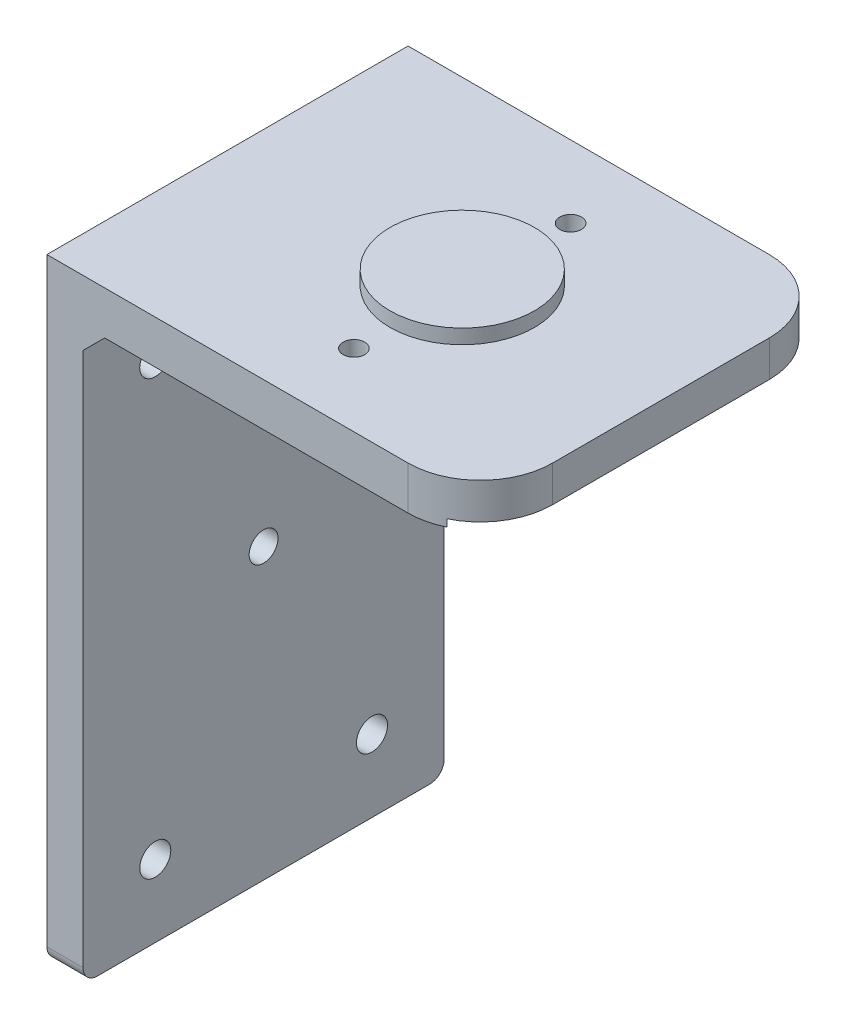
SolidWorks part; units mm, degrees
ref_plane "前视基准面" through (0, 0, 0) normal (0, 0, 1) x (1, 0, 0)
ref_plane "上视基准面" through (0, 0, 0) normal (0, 1, 0) x (1, 0, 0)
ref_plane "右视基准面" through (0, 0, 0) normal (1, 0, 0) x (0, 0, -1)
sketch "草图1" plane through (0, 0, 0) normal (0, 1, 0) x (1, 0, 0)
  line L0 (-77.7657, 2.921) -> (-12.7657, 2.921)
  line L1 (2.2343, -12.079) -> (2.2343, -32.079)
  line L2 (-12.7657, -47.079) -> (-77.7657, -47.079)
  line L3 (-77.7657, -47.079) -> (-77.7657, 2.921)
  line L4 (-45.2657, 0.421) -> (-45.2657, -7.079)
  line L6 (-67.7657, 2.921) -> (-67.7657, -47.079)
  line L7 (-45.2657, -44.579) -> (-45.2657, -37.079)
  circle A1 centre (-45.2657, -22.079) radius 22.5
  circle A3 centre (-45.2657, -37.079) radius 1.5
  circle A4 centre (-45.2657, -22.079) radius 10
  arc A5 (2.2343, -32.079) -> (-12.7657, -47.079) centre (-12.7657, -32.079) cw
  arc A6 (-12.7657, 2.921) -> (2.2343, -12.079) centre (-12.7657, -12.079) cw
  circle A7 centre (-45.2657, -7.079) radius 1.5
  point P8 (2.2343, -47.079)
  point P17 (2.2343, 2.921)
  dimension "D3" = 15
  dimension "D4" = 3
  dimension "D5" = 3
  dimension "D6" = 20
  dimension "D1" = 80
  dimension "D2" = 50
extrude "凸台-拉伸2" add sketch "草图1" along normal blind 5
sketch "草图3" plane through (0, 0, 0) normal (0, -1, 0) x (1, 0, 0)
  line L0 (-77.7657, 47.079) -> (-72.7657, 47.079)
  line L1 (-72.7657, 47.079) -> (-72.7657, -2.921)
  line L2 (-77.7657, -2.921) -> (-12.7657, -2.921) construction
  line L3 (-72.7657, -2.921) -> (-77.7657, -2.921)
  line L5 (-77.7657, -2.921) -> (-77.7657, 47.079)
extrude "凸台-拉伸4" add sketch "草图3" along normal blind 80
sketch "草图4" plane through (-72.7657, 0, 0) normal (1, 0, 0) x (0, 0, -1)
  line L0 (-47.079, -40) -> (2.921, -40)
  line L1 (-47.079, -80) -> (-47.079, 0) construction
  line L2 (2.921, -80) -> (2.921, 0) construction
  circle A0 centre (-22.079, -40) radius 2
  dimension "D1" = 4
extrude "切除-拉伸1" cut sketch "草图4" against normal blind 40 contours A0
sketch "草图6" plane through (-72.7657, 0, 0) normal (1, 0, 0) x (0, 0, -1)
  line L2 (-47.079, -40) -> (2.921, -40)
  line L3 (-47.079, -80) -> (-47.079, 0) construction
  line L4 (2.921, -80) -> (2.921, 0) construction
sketch "草图7" plane through (-72.7657, 0, 0) normal (1, 0, 0) x (0, 0, -1)
  line L0 (2.921, 0) -> (2.921, -10)
  line L1 (2.921, -80) -> (2.921, 0) construction
  line L2 (2.921, -10) -> (-7.079, -10)
  line L3 (2.921, -40) -> (-47.079, -40)
  line L4 (-47.079, -80) -> (-47.079, 0) construction
  line L5 (-22.079, -40) -> (-22.079, 0)
  line L6 (2.921, 0) -> (-47.079, 0) construction
  circle A0 centre (-7.079, -10) radius 2.15
  circle A4 centre (-37.079, -10) radius 2.15
  circle A5 centre (-7.079, -70) radius 2.15
  circle A6 centre (-37.079, -70) radius 2.15
  dimension "D1" = 4.3
extrude "切除-拉伸2" cut sketch "草图7" against normal through all contours A4 | A0 | A5 | A6
sketch "草图12" plane through (0, 0, 0) normal (0, -1, 0) x (1, 0, 0)
  line L0 (-22.7657, 22.079) -> (-17.7657, 22.079)
  line L2 (-17.7657, 47.079) -> (-17.7657, -2.921)
  line L3 (-72.7657, -2.921) -> (-12.7657, -2.921) construction
  line L4 (-22.7657, -2.921) -> (-12.7657, -2.921)
  line L5 (-12.7657, 47.079) -> (-72.7657, 47.079) construction
  circle A0 centre (-45.2657, 22.079) radius 22.5
  line M6 (-72.7657, -2.921) -> (-12.7657, -2.921)
  arc M7 (-12.7657, -2.921) -> (2.2343, 12.079) centre (-12.7657, 12.079) ccw
  line M8 (2.2343, 12.079) -> (2.2343, 32.079)
  arc M9 (2.2343, 32.079) -> (-12.7657, 47.079) centre (-12.7657, 32.079) ccw
  line M10 (-12.7657, 47.079) -> (-72.7657, 47.079)
  dimension "D1" = 45
extrude "切除-拉伸3" cut sketch "草图12" against normal blind 10 contours L2 M10 M6 M7 M8 M9
fillet "圆角2" radius 2 2 edges at (-75.2657, -80, 47.079) (-75.2657, -80, -2.921)
sketch "草图13" plane through (-72.7657, 0, 0) normal (1, 0, 0) x (0, 0, -1)
  line L0 (2.921, 0) -> (2.921, -4)
  line L1 (2.921, -78) -> (2.921, 0) construction
  line L2 (2.921, -4) -> (-47.079, -4)
  line L3 (-47.079, -78) -> (-47.079, 0) construction
  line L4 (-47.079, -4) -> (-47.079, 0)
  line L5 (-47.079, 0) -> (2.921, 0)
extrude "凸台-拉伸5" add sketch "草图13" along normal blind 4
sketch "草图14" plane through (0, 0, -2.921) normal (0, 0, -1) x (-1, 0, 0)
  line L0 (68.7657, 0) -> (72.7657, -4)
  line L1 (72.7657, -4) -> (68.7657, -4)
  line L2 (68.7657, -4) -> (68.7657, 0)
extrude "切除-拉伸4" cut sketch "草图14" against normal through all contours L1 L2 L0
sketch "草图16" plane through (0, 0, 0) normal (0, -1, 0) x (1, 0, 0)
  line L0 (-17.7657, -2.921) -> (-17.7657, -1.921)
  line L1 (-17.7657, 47.079) -> (-17.7657, -2.921) construction
  line L2 (-17.7657, -1.921) -> (-18.7657, -1.921)
  line L3 (-18.7657, -1.921) -> (-18.7657, -2.921)
  line L4 (-68.7657, -2.921) -> (-17.7657, -2.921) construction
  line L5 (-18.7657, -2.921) -> (-17.7657, -2.921)
extrude "凸台-拉伸6" add sketch "草图16" along normal blind 1
sketch "草图17" plane through (-18.7657, 0, 0) normal (-1, 0, 0) x (0, 0, 1)
  line L0 (-1.921, 0) -> (-1.921, -1)
  line L1 (-1.921, -1) -> (-2.921, -1)
  line L2 (-2.921, -1) -> (-2.921, 0)
  line L3 (-2.921, 0) -> (-1.921, 0)
extrude "凸台-拉伸7" add sketch "草图17" along normal blind 55
sketch "草图19" plane through (0, 0, 0) normal (0, -1, 0) x (1, 0, 0)
  line L0 (-17.7657, 47.079) -> (-17.7657, 46.079)
  line L1 (-17.7657, 47.079) -> (-17.7657, -1.921) construction
  line L2 (-17.7657, 46.079) -> (-18.7657, 46.079)
  line L3 (-18.7657, 46.079) -> (-18.7657, 47.079)
  line L4 (-17.7657, 47.079) -> (-68.7657, 47.079) construction
  line L5 (-18.7657, 47.079) -> (-17.7657, 47.079)
extrude "凸台-拉伸8" add sketch "草图19" along normal blind 1
sketch "草图20" plane through (-18.7657, 0, 0) normal (-1, 0, 0) x (0, 0, 1)
  line L0 (47.079, -1) -> (46.079, -1)
  line L1 (46.079, -1) -> (46.079, 0)
  line L2 (46.079, 0) -> (47.079, 0)
  line L3 (47.079, 0) -> (47.079, -1)
extrude "凸台-拉伸9" add sketch "草图20" along normal blind 55
fillet "圆角3" radius 10 2 edges at (-17.7657, 2, -2.921) (-17.7657, 2, 47.079)
sketch "草图21" plane through (0, 5, 0) normal (0, 1, 0) x (1, 0, 0)
  circle A0 centre (-45.2657, -22.079) radius 10
extrude "凸台-拉伸10" add sketch "草图21" along normal blind 2 separate body
